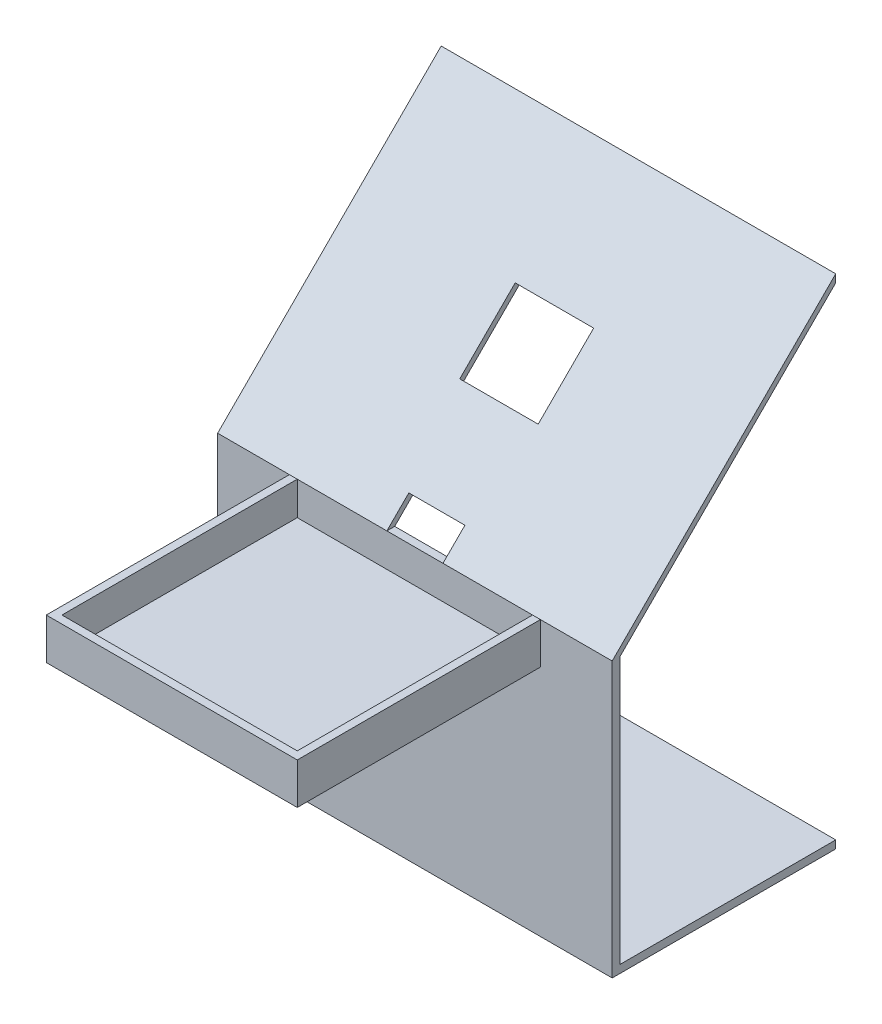
SolidWorks part; units mm, degrees
material "Acrílico (Impacto medio-alto)"
ref_plane "Alzado" through (0, 0, 0) normal (0, 0, 1) x (1, 0, 0)
ref_plane "Planta" through (0, 0, 0) normal (0, 1, 0) x (1, 0, 0)
ref_plane "Vista lateral" through (0, 0, 0) normal (1, 0, 0) x (0, 0, -1)
sketch "Croquis1" plane through (0, 0, 0) normal (0, 1, 0) x (1, 0, 0)
  line L1 (-50.3, 27.5) -> (50.3, 27.5)
  line L2 (-50.3, 27.5) -> (-50.3, -27.5)
  line L3 (-50.3, -27.5) -> (50.3, -27.5)
  line L4 (50.3, 27.5) -> (50.3, -27.5)
  line L5 (-50.3, 27.5) -> (50.3, -27.5) construction
  line L6 (-50.3, -27.5) -> (50.3, 27.5) construction
  point P0 (0, 0)
  dimension "D1" = 100.6
  dimension "D2" = 55
extrude "Saliente-Extruir1" add sketch "Croquis1" along normal blind 2
sketch "Croquis2" plane through (0, 0, 0) normal (0, -1, 0) x (-1, 0, 0)
  line L0 (50.3, -27.5) -> (-50.3, -27.5)
  line L1 (-50.3, -27.5) -> (-50.3, -29.5)
  line L2 (-50.3, -29.5) -> (50.3, -29.5)
  line L3 (50.3, -29.5) -> (50.3, -27.5)
  dimension "D1" = 2
extrude "Saliente-Extruir2" add sketch "Croquis2" against normal blind 70
sketch "Croquis3" plane through (50.3, 0, 0) normal (1, 0, 0) x (0, 0, -1)
  line L0 (-29.5, 70) -> (27.5, 127)
  line L1 (-27.5, 70) -> (-29.5, 70) construction
  line L3 (-27.5, 70) -> (27.5, 125)
  line L4 (27.5, 127) -> (27.5, 125)
  line L5 (-29.5, 70) -> (-27.5, 70)
  line L6 (27.5, 2) -> (27.5, 0) construction
  dimension "D1" = 45
  dimension "D3" = 77.7817
  dimension "D2" = 80.6102
  dimension "D4" = 90
extrude "Saliente-Extruir3" add sketch "Croquis3" against normal up to vertex (100.6 mm away)
sketch "Croquis4" plane through (0, 49.75, 49.75) normal (0, 0.7071, 0.7071) x (1, 0, 0)
  line L0 (-50.3, 109.248) -> (-50.3, 28.6378) construction
  line L1 (-50.3, 28.6378) -> (50.3, 28.6378) construction
  line L2 (-50.3, 68.9429) -> (0, 68.9429) construction
  line L3 (0, 68.9429) -> (0, 28.6378) construction
  line L4 (-5, 28.6378) -> (-5, 34.2378)
  line L5 (-10, 78.9429) -> (10, 78.9429)
  line L6 (-10, 78.9429) -> (-10, 58.9429)
  line L7 (-10, 58.9429) -> (10, 58.9429)
  line L8 (10, 78.9429) -> (10, 58.9429)
  line L9 (-10, 78.9429) -> (10, 58.9429) construction
  line L10 (-10, 58.9429) -> (10, 78.9429) construction
  line L12 (-5, 28.6378) -> (5, 28.6378)
  line L14 (-5, 34.2378) -> (5, 34.2378)
  line L15 (5, 28.6378) -> (5, 34.2378)
  dimension "D1" = 20
  dimension "D2" = 20
  dimension "D3" = 10
  dimension "D4" = 5
  dimension "D5" = 5.6
extrude "Cortar-Extruir1" cut sketch "Croquis4" against normal up to surface (1.4142 mm away) up to face at (0, 97.5, 0)
sketch "Croquis5" plane through (0, 0, 29.5) normal (0, 0, 1) x (1, 0, 0)
  line L0 (-5, 70) -> (5, 70) construction
  circle A0 centre (0, 51) radius 1.5
  point P2 (0, 70)
  dimension "D2" = 3
  dimension "D3" = 51
  dimension "D1" = 19
extrude "Cortar-Extruir2" cut sketch "Croquis5" against normal up to surface (2 mm away) up to face at (-8.3833, 58.6667, 27.5)
sketch "Croquis6" plane through (0, 0, 29.5) normal (0, 0, 1) x (1, 0, 0)
  line L1 (-30, 61.5) -> (30, 61.5)
  line L2 (-30, 61.5) -> (-30, 59.5)
  line L3 (-30, 59.5) -> (30, 59.5)
  line L4 (30, 61.5) -> (30, 59.5)
  line L5 (-30, 61.5) -> (30, 59.5) construction
  line L6 (-30, 59.5) -> (30, 61.5) construction
  line L7 (-5, 70) -> (5, 70) construction
  point P0 (0, 60.5)
  dimension "D1" = 60
  dimension "D2" = 2
  dimension "D3" = 9.5
extrude "Saliente-Extruir4" add sketch "Croquis6" along normal blind 60
sketch "Croquis7" plane through (0, 0, 89.5) normal (0, 0, 1) x (1, 0, 0)
  line L0 (30, 59.5) -> (32, 59.5)
  line L1 (32, 59.5) -> (32, 70)
  line L2 (50.3, 70) -> (5, 70) construction
  line L3 (32, 70) -> (30, 70)
  line L4 (30, 70) -> (30, 59.5)
  line L5 (-30, 70) -> (-32, 70)
  line L7 (-5, 70) -> (-50.3, 70) construction
  line L8 (-32, 70) -> (-32, 59.5)
  line L9 (-32, 59.5) -> (-30, 59.5)
  line L10 (-30, 59.5) -> (-30, 70)
  dimension "D1" = 2
  dimension "D2" = 2
extrude "Saliente-Extruir5" add sketch "Croquis7" against normal up to surface (60 mm away) up to face at (0, 46.6667, 29.5)
sketch "Croquis8" plane through (0, 59.5, 0) normal (0, -1, 0) x (-1, 0, 0)
  line L0 (32, -89.5) -> (32, -91.5)
  line L1 (32, -91.5) -> (-32, -91.5)
  line L2 (-32, -91.5) -> (-32, -89.5)
  line L3 (-32, -89.5) -> (32, -89.5)
  dimension "D1" = 2
extrude "Saliente-Extruir6" add sketch "Croquis8" against normal up to surface (10.5 mm away) up to face at (-31, 70, 59.5)
sketch "Croquis9" plane through (0, 0, 27.5) normal (0, 0, -1) x (-1, 0, 0)
  line L0 (-5, 70) -> (-5, 68)
  line L1 (-5, 68) -> (5, 68)
  line L2 (5, 68) -> (5, 70)
  line L3 (5, 70) -> (-5, 70)
  dimension "D1" = 2
extrude "Saliente-Extruir7" add sketch "Croquis9" against normal blind 2
sketch "Croquis10" plane through (0, 0, 29.5) normal (0, 0, 1) x (1, 0, 0)
  line L0 (-5, 70) -> (-5, 75.6)
  line L1 (-5, 75.6) -> (5, 75.6)
  line L2 (5, 75.6) -> (5, 70)
  line L3 (5, 70) -> (-5, 70)
  dimension "D1" = 5.6
extrude "Cortar-Extruir3" cut sketch "Croquis10" against normal blind 11
sketch "Croquis11" plane through (0, 0, 29.5) normal (0, 0, 1) x (1, 0, 0)
  line L0 (0, 75.6) -> (7.15, 75.6)
  line L1 (5, 75.6) -> (-5, 75.6) construction
  line L2 (7.15, 75.6) -> (7.15, 70)
  line L3 (30, 70) -> (5, 70) construction
  line L4 (7.15, 70) -> (-7.15, 70)
  line L5 (-5, 70) -> (-30, 70) construction
  line L6 (-7.15, 70) -> (-7.15, 75.6)
  line L7 (-7.15, 75.6) -> (0, 75.6)
  dimension "D1" = 7.15
  dimension "D2" = 7.15
extrude "Cortar-Extruir4" cut sketch "Croquis11" against normal blind 10
